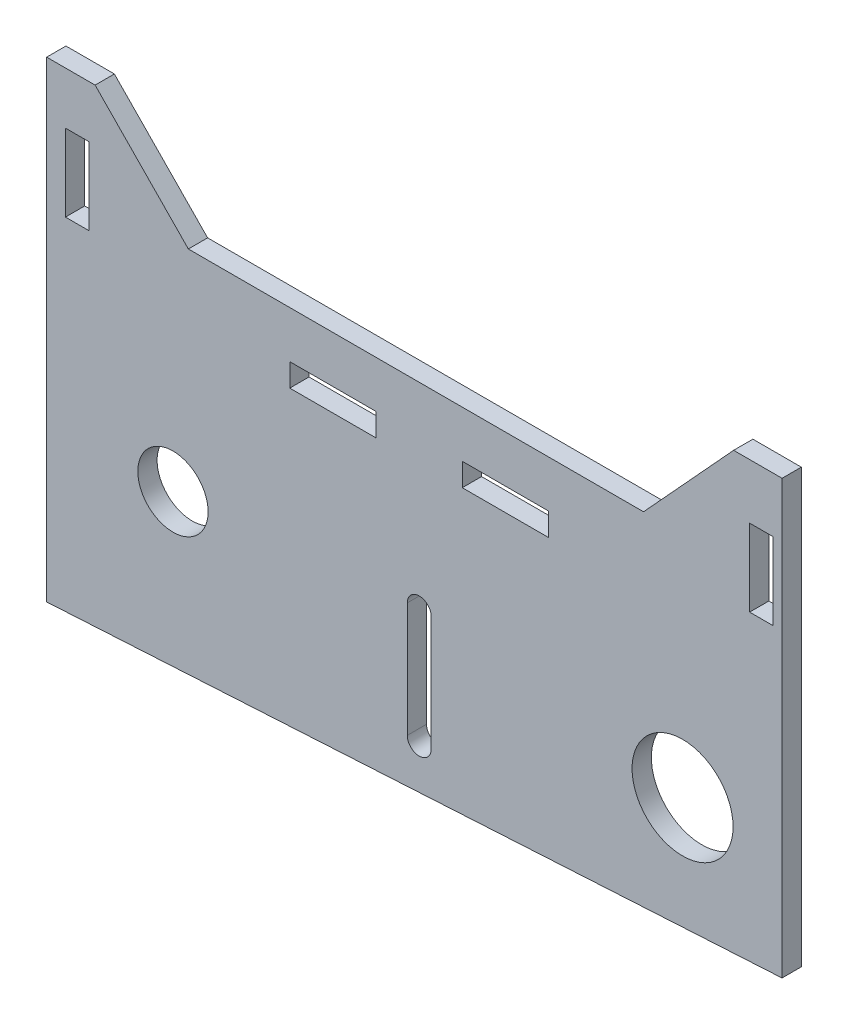
SolidWorks part; units mm, degrees
ref_plane "Front Plane" through (0, 0, 0) normal (0, 0, 1) x (1, 0, 0)
ref_plane "Top Plane" through (0, 0, 0) normal (0, 1, 0) x (1, 0, 0)
ref_plane "Right Plane" through (0, 0, 0) normal (1, 0, 0) x (0, 0, -1)
sketch "Sketch2" plane through (0, 0, 0) normal (0, 0, 1) x (1, 0, 0)
  line L0 (-66.4084, -37.4733) -> (-66.4084, 53.1267)
  line L2 (74.7905, 53.6991) -> (74.7905, -29.4009)
  line L3 (-66.4084, -37.4733) -> (74.7905, -29.4009)
  line L4 (-66.4084, 53.1267) -> (-57.1084, 53.1267)
  line L5 (-57.1084, 53.1267) -> (-39.2067, 34.8267)
  line L6 (-39.2067, 34.8267) -> (48.1933, 34.8267)
  line L7 (48.1933, 34.8267) -> (65.4905, 53.6991)
  line L8 (65.4905, 53.6991) -> (74.7905, 53.6991)
  line L9 (5.1285, 51.2939) -> (5.1285, -54.8027) construction
  line L10 (-62.8084, 28.3267) -> (-58.3084, 28.3267)
  line L11 (-62.8084, 28.3267) -> (-62.8084, 43.1267)
  line L12 (-62.8084, 43.1267) -> (-58.3084, 43.1267)
  line L13 (-58.3084, 28.3267) -> (-58.3084, 43.1267)
  line L14 (-62.8084, 28.3267) -> (-58.3084, 43.1267) construction
  line L15 (-62.8084, 43.1267) -> (-58.3084, 28.3267) construction
  line L16 (73.0654, 43.1267) -> (68.5654, 43.1267)
  line L17 (68.5654, 28.3267) -> (68.5654, 43.1267)
  line L18 (73.0654, 28.3267) -> (68.5654, 28.3267)
  line L19 (73.0654, 28.3267) -> (73.0654, 43.1267)
  line L20 (-19.7334, 25.8267) -> (-3.1334, 25.8267)
  line L21 (29.9905, 21.4267) -> (13.3905, 21.4267)
  line L22 (29.9905, 21.4267) -> (29.9905, 25.8267)
  line L23 (29.9905, 25.8267) -> (13.3905, 25.8267)
  line L24 (13.3905, 21.4267) -> (13.3905, 25.8267)
  line L25 (29.9905, 21.4267) -> (13.3905, 25.8267) construction
  line L26 (29.9905, 25.8267) -> (13.3905, 21.4267) construction
  line L27 (-3.1334, 21.4267) -> (-3.1334, 25.8267)
  line L28 (-19.7334, 21.4267) -> (-3.1334, 21.4267)
  line L29 (-19.7334, 21.4267) -> (-19.7334, 25.8267)
  line L30 (5.1285, -3.0019) -> (5.1285, -25.0371) construction
  line L31 (7.4285, -3.0019) -> (7.4285, -25.0371)
  line L32 (2.8285, -3.0019) -> (2.8285, -25.0371)
  arc A0 (7.4285, -3.0019) -> (2.8285, -3.0019) centre (5.1285, -3.0019) ccw
  arc A1 (2.8285, -25.0371) -> (7.4285, -25.0371) centre (5.1285, -25.0371) ccw
  circle A2 centre (55.6905, -8.9577) radius 9.7
  circle A3 centre (-42.1584, -6.9895) radius 6.75
  point P3 (-66.4084, 7.8267)
  point P5 (-60.5584, 35.7267)
  point P20 (21.6905, 23.6267)
  point P31 (5.1285, -14.0195)
  point P36 (5.1285, -27.3371)
  point P37 (4.191, -33.4371)
  point P42 (0, 0)
  point P43 (0, 0)
  point P45 (-37.0491, -30.9057)
  dimension "D18" = 19.4
  dimension "D21" = 13.5
  dimension "D22" = 24.25
  dimension "D1" = 90.6
  dimension "D2" = 83.1
  dimension "D3" = 141.2
  dimension "D4" = 9.3
  dimension "D5" = 87.4
  dimension "D6" = 25.6
  dimension "D7" = 18.3
  dimension "D8" = 14.8
  dimension "D9" = 4.5
  dimension "D10" = 10
  dimension "D11" = 3.6
  dimension "D12" = 16.6
  dimension "D13" = 4.4
  dimension "D14" = 44.8
  dimension "D15" = 9
  dimension "D16" = 6.1
  dimension "D17" = 4.6
  dimension "D19" = 19.1
  dimension "D20" = 21.5
  dimension "D23" = 29.05
extrude "Boss-Extrude1" add sketch "Sketch2" along normal blind 3.7
